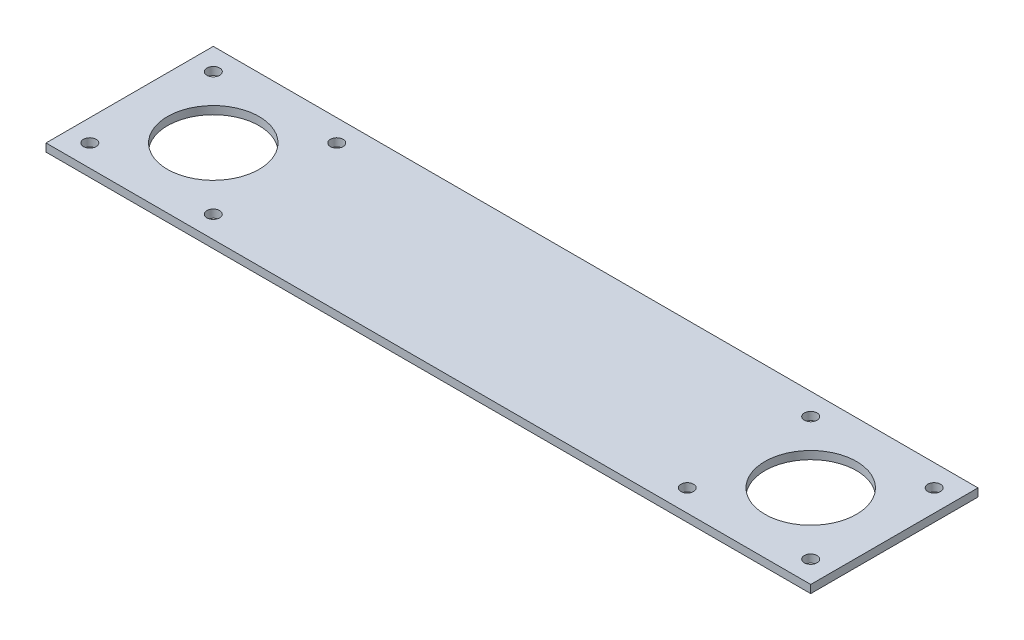
SolidWorks part; units mm, degrees
ref_plane "Front Plane" through (0, 0, 0) normal (0, 0, 1) x (1, 0, 0)
ref_plane "Top Plane" through (0, 0, 0) normal (0, 1, 0) x (1, 0, 0)
ref_plane "Right Plane" through (0, 0, 0) normal (1, 0, 0) x (0, 0, -1)
sketch "Sketch1" plane through (0, 0, 0) normal (0, 1, 0) x (1, 0, 0)
  line L0 (0, -55) -> (0, 55) construction
  line L1 (-140, -21) -> (140, -21)
  line L2 (-140, -21) -> (-140, 21)
  line L3 (-140, 21) -> (140, 21)
  line L4 (140, -21) -> (140, 21)
  line L5 (-140, -21) -> (140, 21) construction
  line L6 (-140, 21) -> (140, -21) construction
  line L7 (-96, 21) -> (-54, 21) construction
  line L8 (-96, 21) -> (-96, -21)
  line L9 (-96, -21) -> (-54, -21) construction
  line L10 (-54, 21) -> (-54, -21) construction
  line L11 (-96, 21) -> (-54, -21) construction
  line L12 (-96, -21) -> (-54, 21) construction
  line L13 (96, -21) -> (54, 21) construction
  line L14 (96, 21) -> (54, -21) construction
  line L15 (54, 21) -> (54, -21) construction
  line L16 (96, -21) -> (54, -21) construction
  line L17 (96, 21) -> (96, -21)
  line L18 (96, 21) -> (54, 21) construction
  line L19 (-12.5, 0) -> (12.5, 0) construction
  circle A0 centre (-75, 0) radius 62.5 construction
  circle A1 centre (-59.5, 15.5) radius 1.6
  circle A2 centre (-59.5, -15.5) radius 1.6
  circle A3 centre (-90.5, -15.5) radius 1.6
  circle A4 centre (-90.5, 15.5) radius 1.6
  circle A5 centre (75, 0) radius 62.5 construction
  circle A6 centre (90.5, 15.5) radius 1.6
  circle A7 centre (90.5, -15.5) radius 1.6
  circle A8 centre (59.5, -15.5) radius 1.6
  circle A9 centre (59.5, 15.5) radius 1.6
  circle A10 centre (0, 0) radius 25 construction
  circle A11 centre (-75, 0) radius 11.5
  circle A12 centre (75, 0) radius 11.5
  point P0 (0, 0)
  point P23 (-75, 0)
  point P43 (75, 0)
  dimension "D3" = 125
  dimension "D5" = 3.2
  dimension "D8" = 150
  dimension "D10" = 50
  dimension "D11" = 23
  dimension "D1" = 42
  dimension "D2" = 280
  dimension "D4" = 42
  dimension "D7" = 31
  dimension "D9" = 25
  dimension "D6" = 4
extrude "Boss-Extrude1" add sketch "Sketch1" along normal blind 2 contours L17 L3 L8 L1 A8 A6 A4 A3 A2 A1 A7 A9
